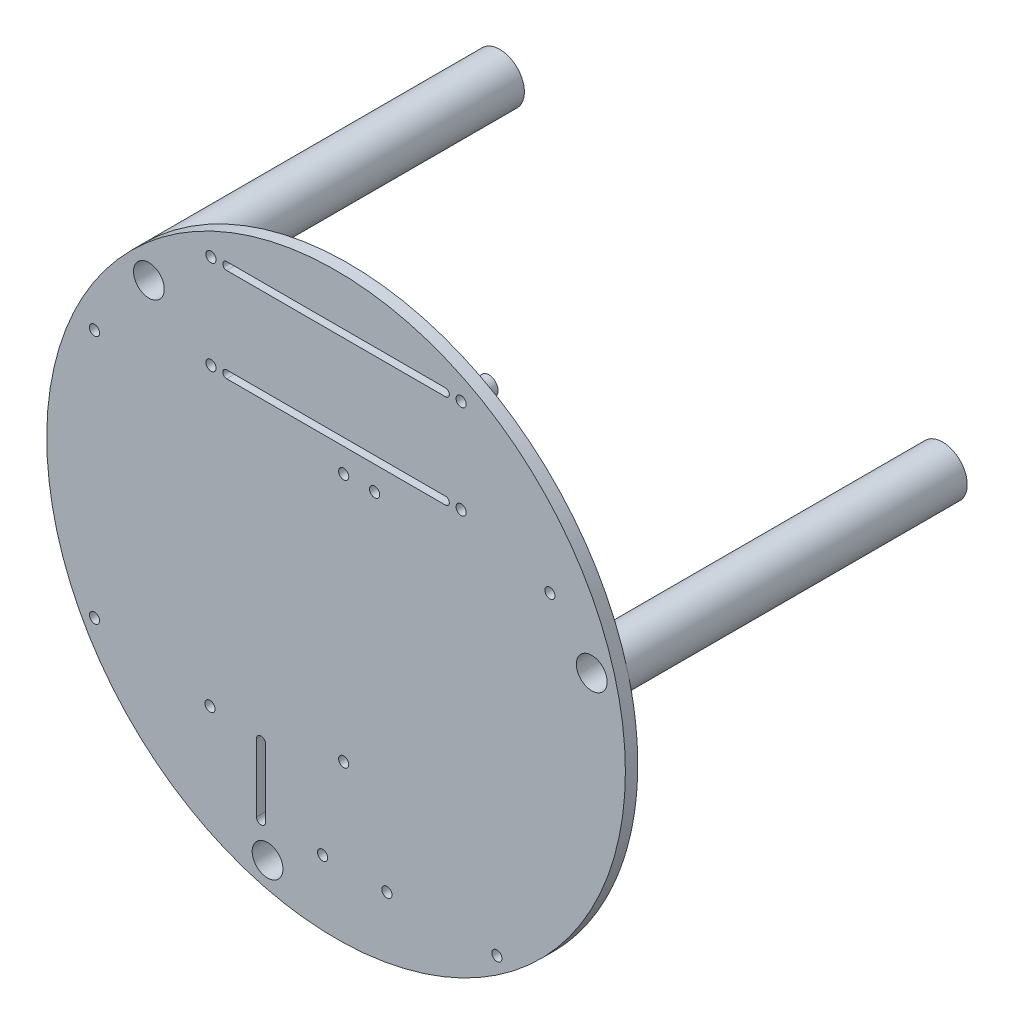
SolidWorks part; units mm, degrees
ref_plane "Plan de face" through (0, 0, 0) normal (0, 0, 1) x (1, 0, 0)
ref_plane "Plan de dessus" through (0, 0, 0) normal (0, 1, 0) x (1, 0, 0)
ref_plane "Plan de droite" through (0, 0, 0) normal (1, 0, 0) x (0, 0, -1)
sketch "Sketch1" plane through (0, 0, 0) normal (0, 0, 1) x (1, 0, 0)
  circle A0 centre (0, 0) radius 47
  dimension "D1" = 94
extrude "Boss-Extrude1" add sketch "Sketch1" along normal blind 2
sketch "Sketch3" plane through (0, 0, 0) normal (0, 0, -1) x (-1, 0, 0)
  line L0 (0, 0) -> (0, 43) construction
  line L1 (0, 0) -> (30.4056, 30.4056) construction
  circle A0 centre (0, 0) radius 43 construction
  circle A1 centre (30.4056, 30.4056) radius 2.5
  circle A2 centre (11.1292, -41.5348) radius 2.5
  circle A3 centre (-41.5348, 11.1292) radius 2.5
  point P13 (0, 0)
  dimension "D1" = 86
  dimension "D2" = 5
  dimension "D3" = 45
  dimension "D4" = 3
extrude "Cut-Extrude1" cut sketch "Sketch3" against normal through all contours A3 | A1 | A2
sketch "Sketch5" plane through (0, 0, 0) normal (0, 0, -1) x (-1, 0, 0)
  circle A0 centre (30.4056, 30.4056) radius 2.5 construction
  circle A1 centre (30.4056, 30.4056) radius 2.5
  circle A2 centre (30.4056, 30.4056) radius 4
  circle A3 centre (11.1292, -41.5348) radius 4
  circle A4 centre (11.1292, -41.5348) radius 2.5
  circle A5 centre (-41.5348, 11.1292) radius 4
  circle A6 centre (-41.5348, 11.1292) radius 2.5
  point P13 (0, 0)
  dimension "D1" = 8
  dimension "D2" = 5
  dimension "D3" = 3
extrude "Boss-Extrude2" add sketch "Sketch5" along normal blind 55
sketch "Sketch2" plane through (0, 0, 2) normal (0, 0, 1) x (1, 0, 0)
  line L0 (0, 40) -> (0, 22.24) construction
  line L1 (-21.58, 40) -> (21.58, 40) construction
  line L2 (-21.58, 40) -> (-21.58, 22.24) construction
  line L3 (-21.58, 22.24) -> (21.58, 22.24) construction
  line L4 (21.58, 40) -> (21.58, 22.24) construction
  line L5 (-21.58, 31.12) -> (21.58, 31.12) construction
  line L6 (20.5, 20.24) -> (20.5, -27.76) construction
  line L7 (5, 20.24) -> (36, 20.24) construction
  line L8 (5, 20.24) -> (5, -27.76) construction
  line L9 (5, -27.76) -> (36, -27.76) construction
  line L10 (36, 20.24) -> (36, -27.76) construction
  line L11 (-19, 20.24) -> (-19, -22.76) construction
  line L12 (-40.5, -22.76) -> (2.5, -22.76) construction
  line L13 (-40.5, -22.76) -> (-40.5, 20.24) construction
  line L14 (-40.5, 20.24) -> (2.5, 20.24) construction
  line L15 (2.5, -22.76) -> (2.5, 20.24) construction
  line L16 (-40.5, -1.26) -> (2.5, -1.26) construction
  line L17 (17.78, 23.5) -> (-17.78, 23.5) construction
  line L18 (17.78, 22.875) -> (-17.78, 22.875)
  line L19 (17.78, 24.125) -> (-17.78, 24.125)
  line L20 (17.78, 38.74) -> (-17.78, 38.74) construction
  line L21 (17.78, 39.365) -> (-17.78, 39.365)
  line L22 (17.78, 38.115) -> (-17.78, 38.115)
  circle A0 centre (20.32, 38.74) radius 0.825
  circle A1 centre (20.32, 23.5) radius 0.825
  circle A2 centre (-20.32, 23.5) radius 0.825
  circle A3 centre (-20.32, 38.74) radius 0.825
  circle A4 centre (34.74, 18.98) radius 0.825
  circle A5 centre (6.26, 18.98) radius 0.825
  circle A6 centre (-39.24, 18.98) radius 0.825
  circle A7 centre (1.24, 18.98) radius 0.825
  circle A8 centre (1.24, -21.5) radius 0.825
  circle A9 centre (-39.24, -21.5) radius 0.825
  arc A10 (17.78, 22.875) -> (17.78, 24.125) centre (17.78, 23.5) ccw
  arc A11 (-17.78, 24.125) -> (-17.78, 22.875) centre (-17.78, 23.5) ccw
  arc A12 (17.78, 39.365) -> (17.78, 38.115) centre (17.78, 38.74) cw
  arc A13 (-17.78, 38.115) -> (-17.78, 39.365) centre (-17.78, 38.74) cw
  point P9 (0, 31.12)
  point P46 (0, 23.5)
  point P55 (0, 38.74)
  dimension "D4" = 1.26
  dimension "D6" = 1.65
  dimension "D11" = 1.26
  dimension "D13" = 1.65
  dimension "D18" = 1.26
  dimension "D19" = 1.65
  dimension "D1" = 43.16
  dimension "D2" = 17.76
  dimension "D3" = 40
  dimension "D5" = 1.26
  dimension "D7" = 48
  dimension "D8" = 31
  dimension "D9" = 50
  dimension "D10" = 5
  dimension "D12" = 1.26
  dimension "D14" = 43
  dimension "D15" = 43
  dimension "D16" = 2.5
  dimension "D17" = 2
  dimension "D20" = 1.25
  dimension "D21" = 2.54
  dimension "D22" = 2.54
extrude "Cut-Extrude-Nano+Recto" cut sketch "Sketch2" against normal through all
sketch "Sketch6" plane through (0, 0, 0) normal (0, 0, -1) x (-1, 0, 0)
  circle A0 centre (39.24, -21.5) radius 0.825 construction
  circle A1 centre (-1.24, -21.5) radius 0.825 construction
  circle A2 centre (39.24, 18.98) radius 0.825 construction
  circle A3 centre (-1.24, 18.98) radius 0.825 construction
  circle A4 centre (-6.26, 18.98) radius 0.825 construction
  circle A5 centre (-34.74, 18.98) radius 0.825 construction
  circle A6 centre (-20.32, 23.5) radius 0.825 construction
  circle A7 centre (20.32, 23.5) radius 0.825 construction
  circle A8 centre (20.32, 38.74) radius 0.825 construction
  circle A9 centre (-20.32, 38.74) radius 0.825 construction
  circle A10 centre (39.24, -21.5) radius 0.825
  circle A11 centre (-1.24, -21.5) radius 0.825
  circle A12 centre (39.24, 18.98) radius 0.825
  circle A13 centre (-1.24, 18.98) radius 0.825
  circle A14 centre (-6.26, 18.98) radius 0.825
  circle A15 centre (-34.74, 18.98) radius 0.825
  circle A16 centre (-20.32, 23.5) radius 0.825
  circle A17 centre (20.32, 23.5) radius 0.825
  circle A18 centre (20.32, 38.74) radius 0.825
  circle A19 centre (-20.32, 38.74) radius 0.825
  circle A20 centre (-34.74, 18.98) radius 1.5
  circle A21 centre (-20.32, 23.5) radius 1.5
  circle A22 centre (-20.32, 38.74) radius 1.5
  circle A23 centre (20.32, 23.5) radius 1.5
  circle A24 centre (20.32, 38.74) radius 1.5
  circle A25 centre (-6.26, 18.98) radius 1.5
  circle A26 centre (-1.24, 18.98) radius 1.5
  circle A27 centre (39.24, 18.98) radius 1.5
  circle A28 centre (39.24, -21.5) radius 1.5
  circle A29 centre (-1.24, -21.5) radius 1.5
  dimension "D1" = 3
extrude "Boss-Extrude3" add sketch "Sketch6" along normal blind 2.5
sketch "Sketch4" plane through (0, 0, 0) normal (0, 0, -1) x (-1, 0, 0)
  line L0 (-27.39, -37.6) -> (-27.39, -22) construction
  line L1 (-27.39, -22) -> (-7, -22) construction
  line L2 (-7, -22) -> (-7, -37.6) construction
  line L3 (-7, -37.6) -> (-27.39, -37.6) construction
  line L4 (3.44, -37.6) -> (3.44, -24.56) construction
  line L5 (3.44, -24.56) -> (-7, -24.56) construction
  line L7 (-7, -37.6) -> (3.44, -37.6) construction
  line L8 (-17.195, -22) -> (-17.195, -37.6) construction
  line L9 (12.18, -36.34) -> (12.18, -25.34) construction
  line L12 (11.43, -36.34) -> (11.43, -25.34)
  line L13 (12.93, -36.34) -> (12.93, -25.34)
  circle A0 centre (-8.26, -36.34) radius 0.825
  circle A1 centre (2.18, -36.34) radius 0.825
  circle A2 centre (-26.13, -36.34) radius 0.825
  arc A7 (11.43, -36.34) -> (12.93, -36.34) centre (12.18, -36.34) ccw
  arc A8 (12.93, -25.34) -> (11.43, -25.34) centre (12.18, -25.34) ccw
  circle A9 centre (20.48, -24.54) radius 0.825
  point P18 (12.18, -30.84)
  dimension "D7" = 1.26
  dimension "D11" = 1.65
  dimension "D12" = 1.65
  dimension "D13" = 11
  dimension "D14" = 0.75
  dimension "D16" = 0.8
  dimension "D18" = 1.65
  dimension "D1" = 20.39
  dimension "D2" = 15.6
  dimension "D3" = 13.04
  dimension "D4" = 10.44
  dimension "D5" = 7
  dimension "D6" = 22
  dimension "D8" = 1.26
  dimension "D9" = 1.26
  dimension "D10" = 1.26
  dimension "D15" = 10
  dimension "D17" = 8.3
extrude "Cut-Extrude-Verso" cut sketch "Sketch4" against normal through all
